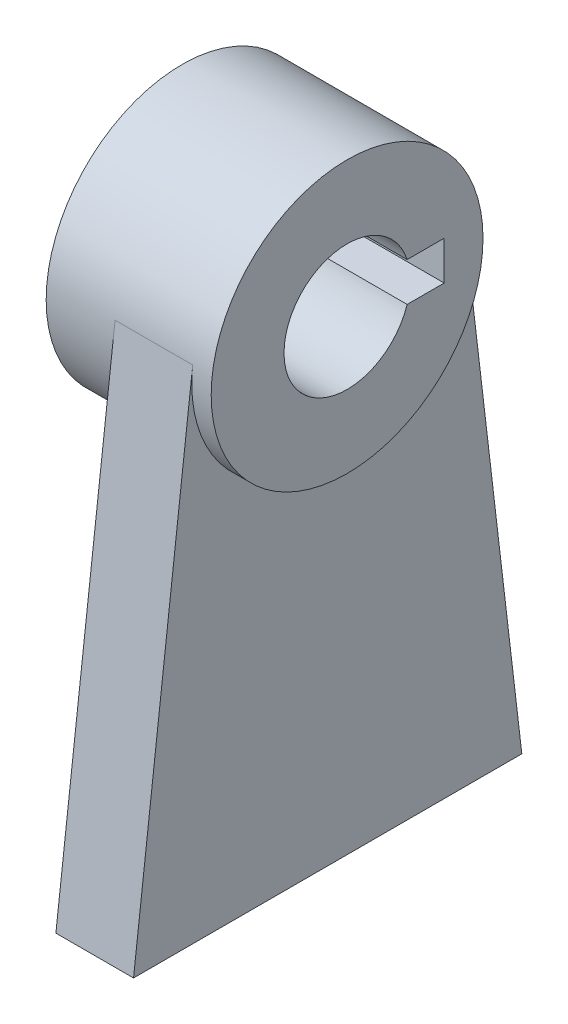
SolidWorks part; units mm, degrees
ref_plane "Alzado" through (0, 0, 0) normal (0, 0, 1) x (1, 0, 0)
ref_plane "Planta" through (0, 0, 0) normal (0, 1, 0) x (1, 0, 0)
ref_plane "Vista lateral" through (0, 0, 0) normal (1, 0, 0) x (0, 0, -1)
sketch "Croquis5" plane through (0, 0, 0) normal (1, 0, 0) x (0, 0, -1)
  line L0 (40, -36) -> (27.8069, 67.2828)
  line L1 (40, -36) -> (-40, -36)
  line L5 (40, -36) -> (-32.3164, 29.0847) construction
  line L6 (32.3164, 29.0847) -> (-40, -36) construction
  line L7 (-40, -36) -> (-27.8069, 67.2828)
  arc A0 (27.8069, 67.2828) -> (-27.8069, 67.2828) centre (0, 64) ccw
  point P0 (0, 0)
  dimension "D3" = 56
  dimension "D1" = 80
extrude "Saliente-Extruir3" add sketch "Croquis5" along normal blind 16
sketch "Croquis6" plane through (16, 0, 0) normal (1, 0, 0) x (0, 0, -1)
  circle A0 centre (0, 64) radius 28
extrude "Saliente-Extruir4" add sketch "Croquis6" along normal blind 4
sketch "Croquis7" plane through (0, 0, 0) normal (-1, 0, 0) x (0, 0, 1)
  circle A0 centre (0, 64) radius 28
extrude "Saliente-Extruir5" add sketch "Croquis7" along normal blind 14
sketch "Croquis8" plane through (20, 0, 0) normal (1, 0, 0) x (0, 0, -1)
  line L1 (20, 68) -> (20, 60)
  line L2 (20, 60) -> (12.3693, 60)
  line L3 (20, 68) -> (12.3693, 68)
  arc A0 (12.3693, 68) -> (12.3693, 60) centre (0, 64) ccw
  point P8 (20, 64)
  dimension "D1" = 26
  dimension "D2" = 20
  dimension "D3" = 8
extrude "Cortar-Extruir1" cut sketch "Croquis8" against normal through all contours A0 L2 L1 L3
